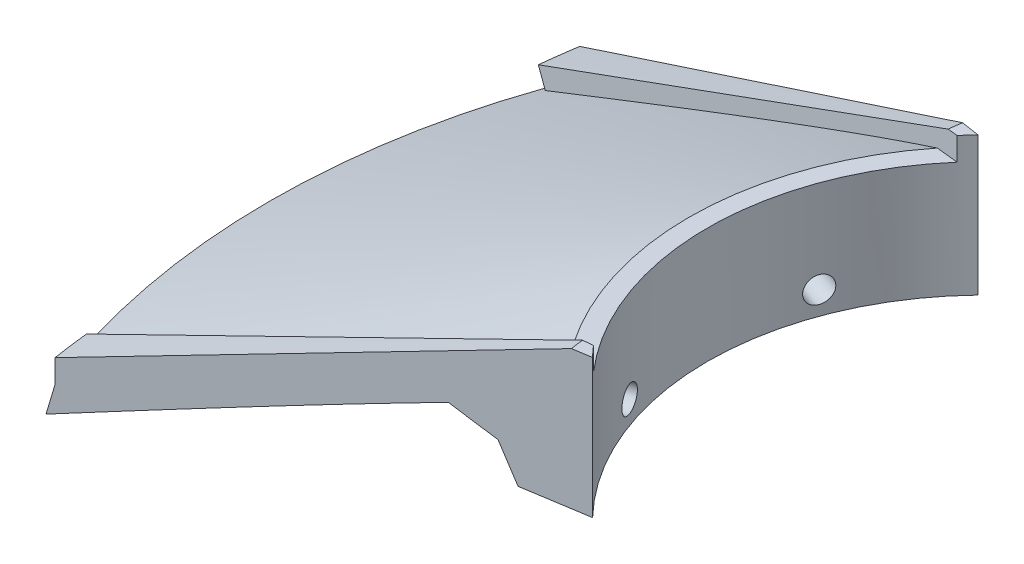
SolidWorks part; units mm, degrees
ref_plane "Piano frontale" through (0, 0, 0) normal (0, 0, 1) x (1, 0, 0)
ref_plane "Piano superiore" through (0, 0, 0) normal (0, 1, 0) x (1, 0, 0)
ref_plane "Piano destro" through (0, 0, 0) normal (1, 0, 0) x (0, 0, -1)
sketch "Schizzo1" plane through (0, 0, 0) normal (0, 0, -1) x (-1, 0, 0)
  line L0 (83.8013, 10.2496) -> (156.3059, -23.5599)
  line L1 (0, 0) -> (60, 0) construction
  line L2 (156.3059, -23.5599) -> (154.6308, -17.2618)
  line L3 (154.6308, -17.2618) -> (64, 25)
  line L4 (0, 0) -> (0, 60.5495) construction
  line L8 (60, 25) -> (64, 25)
  line L9 (60, 25) -> (60, 0)
  line L16 (60, 0) -> (72, 0)
  line L17 (72, 0) -> (75.3441, 7.1714)
  line L18 (75.3441, 7.1714) -> (83.8013, 10.2496)
  dimension "D1" = 25
  dimension "D2" = 4
  dimension "D3" = 5
  dimension "D4" = 25
  dimension "D5" = 12
  dimension "D6" = 45
  dimension "D7" = 9
  dimension "D8" = 60
  dimension "D9" = 80
  dimension "D10" = 100
revolve "Rivoluzione1" add sketch "Schizzo1" angle 44 about L4
sketch "Schizzo6" plane through (0, 25, 0) normal (0, 1, 0) x (1, 0, 0)
  line L0 (-43.1604, 41.6795) -> (-145.2095, 57.8425)
  line L1 (-43.1604, 41.6795) -> (-112.4371, 108.5792)
  line L2 (-43.1604, -41.6795) -> (-145.2095, -57.8425)
  line L3 (-43.1604, -41.6795) -> (-112.4371, -108.5792)
  line L4 (-43.1604, -41.6795) -> (-150.6465, -41.6795) construction
  line L5 (-43.1604, 41.6795) -> (-150.6465, 41.6795) construction
  arc A1 (-112.4371, 108.5792) -> (-112.4371, -108.5792) centre (0, 0) ccw construction
  arc A2 (-112.4371, 108.5792) -> (-145.2095, 57.8425) centre (0, 0) ccw
  arc A3 (-145.2095, -57.8425) -> (-112.4371, -108.5792) centre (0, 0) ccw
  point P3 (0, 0)
  point P15 (-51.9615, -30)
  point P18 (-51.9615, 30)
  dimension "D1" = 35
  dimension "D2" = 35
extrude "Taglio-Estrusione1" cut sketch "Schizzo6" against normal blind 59
sketch "Schizzo2" plane through (7.5375, 0, -33.6497) normal (0.1564, 0, -0.9877) x (-0.9877, 0, -0.1564)
  line L0 (51.3299, 25) -> (51.3299, 30)
  line L1 (51.3299, 25) -> (56.1403, 25)
  line L2 (56.1403, 25) -> (152.9332, -17.2618)
  line L3 (152.9332, -17.2618) -> (154.934, -12.6796)
  line L4 (154.934, -12.6796) -> (55.3299, 30)
  line L5 (55.3299, 30) -> (51.3299, 30)
  line L8 (51.3299, 25) -> (51.3299, 0) construction
  line L11 (2.1807, 0) -> (2.1807, 43.4552) construction
  line L12 (62.1807, 25) -> (38.2896, 25) construction
  line L13 (56.1403, 25) -> (51.3299, 25) construction
  point P2 (60.643, 25)
  point P7 (64, 25)
  point P11 (156.2213, -17.2618)
  point P12 (64.643, 30)
  point P18 (64, 25)
  point P19 (0, 0)
  point P20 (155.9218, -17.2618)
  point P24 (64.7645, 25)
  point P25 (64.2897, 25)
  dimension "D1" = 5
  dimension "D2" = 4
  dimension "D3" = 5
sketch "Schizzo3" plane through (7.5375, 0, 33.6497) normal (0.1564, 0, 0.9877) x (0.9877, 0, -0.1564)
  line L6 (-51.3299, 25) -> (-56.1403, 25)
  line L7 (-56.1403, 25) -> (-152.9332, -17.2618)
  line L8 (-152.9332, -17.2618) -> (-152.9332, -12.2618)
  line L9 (-152.9332, -12.2618) -> (-55.3299, 30)
  line L10 (-55.3299, 30) -> (-51.3299, 30)
  line L11 (-51.3299, 30) -> (-51.3299, 25)
  line L15 (-2.1807, 0) -> (-2.1807, 52.2782) construction
  point P2 (-60.9843, 25)
  point P5 (-64.1363, 25)
  point P7 (-63.8947, 25)
  point P12 (0, 0)
  point P13 (-64, 25)
  point P14 (0, 0)
  point P15 (-155.9218, -17.2618)
  point P16 (-155.9218, -17.2618)
  point P22 (-155.9218, -17.2618)
  point P23 (-155.9218, -17.2618)
  point P24 (-155.9218, -12.2618)
  point P25 (-155.9218, -17.2618)
  point P26 (-63.492, 25)
  dimension "D1" = 5
  dimension "D2" = 5
  dimension "D3" = 4
hole_wizard "Foro per Vite M4-1" positions "Schizzo3D2" profile "Schizzo5" hole size "M4" standard "ISO"
sketch3d "Schizzo3D2"
  line L0 (0, 0, 0) -> (0, 5, 0) construction
  line L1 (0, 25, 0) -> (0, 0, 0) construction
  line L2 (0, 5, 0) -> (-56.3816, 5, 20.5212) construction
  line L5 (0, 5, 0) -> (-56.3816, 5, -20.5212) construction
  line L9 (0, 5, 0) -> (-59.4866, 5, 0) construction
  point P0 (-56.3816, 5, 20.5212)
  point P2 (-56.3816, 5, -20.5212)
  point P25 (0, 0, 0)
  point P26 (-59.4866, 5, 0)
  dimension "D1" = 41.0424
  dimension "D2" = 20
  dimension "D3" = 5
  dimension "D4" = 40
  dimension "D6" = 5
sketch "Schizzo5" plane through (-56.3816, 5, 20.5212) normal (0, 1, 0) x (-0.342, 0, -0.9397)
  line L0 (0, 0) -> (0, 9.7824)
  line L1 (0, 9.7824) -> (2.8, 8.1)
  line L2 (2.8, 8.1) -> (2.8, 0)
  line L5 (2.8, 0) -> (0, 0)
  line L10 (0, 9.7824) -> (-2.8, 8.1) construction
  line L11 (0, -6.35) -> (0, 107.95) construction
  dimension "Hole Dia." = 5.6
  dimension "Hole Depth" = 8.1
  dimension "Drill Angle" = 118
revolve "Rivoluzione2" add sketch "Schizzo2" angle 3 about L11
revolve "Rivoluzione3" add sketch "Schizzo3" angle 3 about L15
sketch "Schizzo7" plane through (0, 30, 0) normal (0, 1, 0) x (1, 0, 0)
  circle A0 centre (0, 0) radius 60
extrude "Taglio-Estrusione2" cut sketch "Schizzo7" against normal blind 59
